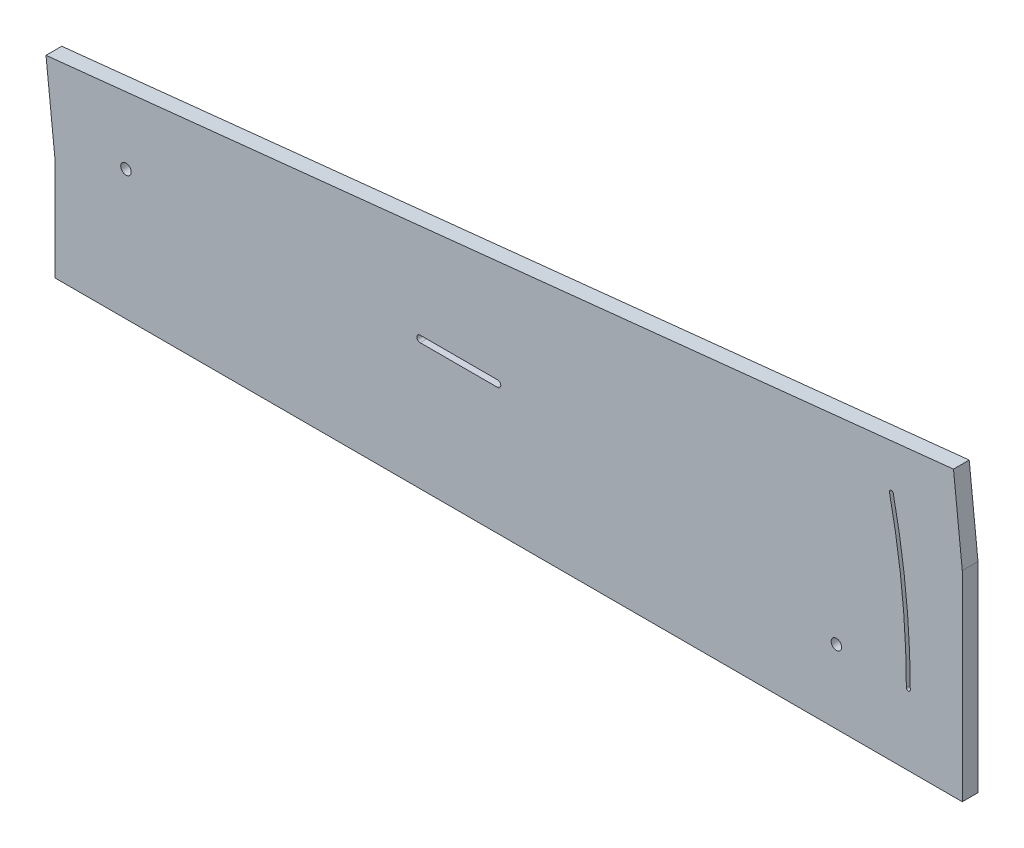
SolidWorks part; units mm, degrees
material "Pine"
ref_plane "Front Plane" through (0, 0, 0) normal (0, 0, 1) x (1, 0, 0)
ref_plane "Top Plane" through (0, 0, 0) normal (0, 1, 0) x (1, 0, 0)
ref_plane "Right Plane" through (0, 0, 0) normal (1, 0, 0) x (0, 0, -1)
sketch "Sketch1" plane through (0, 0, 0) normal (0, 0, 1) x (1, 0, 0)
  line L0 (-10.6201, 228.0434) -> (1088.2272, 343.5369)
  line L1 (1088.2272, 343.5369) -> (1098.8472, 242.4935)
  line L2 (1098.8472, 242.4935) -> (0, 127) construction
  line L3 (0, 127) -> (-10.6201, 228.0434)
  line L4 (0, 127) -> (0, 0)
  line L5 (0, 0) -> (1098.8472, 0)
  line L6 (1098.8472, 0) -> (1098.8472, 242.4935)
  line L7 (0, 127) -> (1098.8472, 127) construction
  dimension "D1" = 1104.9
  dimension "D2" = 101.6
  dimension "D3" = 6
  dimension "D4" = 127
extrude "Boss-Extrude1" add sketch "Sketch1" along normal blind 19.05
sketch "Sketch3" [suppressed] plane through (0, 0, 19.05) normal (0, 0, 1) x (1, 0, 0)
  line L0 (93.1354, -242.5766) -> (408.4688, -242.5766) construction
  line B0 (221.5466, -65.8912) -> (52.3501, -63.5412)
  arc B1 (731.486, 25.7569) -> (660.9874, 53.9563) centre (734.4449, 135.377) cw
  spline B2 degree 3 poles (52.3501, -63.5412) (59.4, -57.2747) (64.9444, -48.7137) (73.4997, -44.7416) (87.4583, -38.2608) (102.9844, -35.6165) (118.1487, -32.9919) (143.8059, -28.5512) (169.9355, -27.3805) (195.6971, -23.5921) (196.7931, -23.4309) (197.0131, -21.6398) (198.0471, -21.2421) (217.473, -13.7706) (237.3699, -7.5641) (256.7958, -0.0926) (257.8298, 0.3051) (258.1296, 1.8164) (259.1458, 2.2574) (299.7181, 19.8642) (340.9438, 35.9565) (381.3433, 53.9563) (420.0735, 71.2124) (456.7375, 93.258) (496.4909, 108.0052) (506.0382, 111.547) (516.883, 108.7307) (527.0402, 108.0052) (528.1452, 107.9263) (528.3844, 106.1195) (529.3902, 105.6552) (548.8157, 96.6896) (568.7134, 88.7714) (588.1389, 79.8058) (589.1448, 79.3416) (589.5464, 78.038) (590.4889, 77.4558) (616.2054, 61.5721) (640.7876, 43.5367) (668.0373, 30.4568) (680.3702, 24.537) (694.3438, 22.0676) (707.9865, 21.057) (715.9529, 20.4669) (723.6528, 24.1903) (731.486, 25.7569) knots 0 0 0 0 1 1 1 2 2 2 3 3 3 4 4 4 5 5 5 6 6 6 7 7 7 8 8 8 9 9 9 10 10 10 11 11 11 12 12 12 13 13 13 14 14 14 15 15 15 15
  spline B3 degree 3 poles (660.9874, 53.9563) (664.904, 57.0896) (668.3424, 60.939) (672.7372, 63.3561) (684.0984, 69.6048) (695.5775, 76.0455) (707.9865, 79.8058) (721.6663, 83.9512) (736.1859, 84.5057) (750.2856, 86.8556) knots 0 0 0 0 1 1 1 2 2 2 3 3 3 3
  spline B4 degree 3 poles (750.2856, 86.8556) (751.0689, 86.0723) (751.5704, 84.81) (752.6355, 84.5057) (762.6842, 81.6346) (773.1362, 80.3269) (783.1849, 77.4558) (784.25, 77.1515) (784.5831, 75.6728) (785.5348, 75.1059) (821.429, 53.7222) (856.7292, 31.2479) (893.6326, 11.6572) (920.2584, -2.4775) (948.3154, -13.7409) (975.8809, -25.942) (996.1025, -34.8926) (1017.2003, -41.9018) (1036.9796, -51.7915) (1042.4516, -54.5275) (1045.5354, -60.9541) (1051.0793, -63.5412) (1057.6236, -66.5952) (1065.3776, -65.9574) (1072.2289, -68.2411) (1079.5478, -70.6808) (1088.3258, -71.811) (1093.3784, -77.6409) (1099.3832, -84.5695) (1099.645, -94.8739) (1102.7782, -103.4904) knots 0 0 0 0 1 1 1 2 2 2 3 3 3 4 4 4 5 5 5 6 6 6 7 7 7 8 8 8 9 9 9 10 10 10 10
sketch_block_instance "Block1-1"
sketch_block "Block1"
sketch "Sketch5" [suppressed] plane through (0, 0, 19.05) normal (0, 0, 1) x (1, 0, 0)
  line L0 (13.2751, -329.5043) -> (1112.1224, -329.5043) construction
sketch_block_instance "KSU Logo-1"
sketch_block "KSU Logo"
sketch "Sketch6" [suppressed] plane through (0, 0, 19.05) normal (0, 0, 1) x (1, 0, 0)
  line L0 (13.2751, -329.5043) -> (1112.2917, -329.5043)
  arc A0 (644.4772, -182.5663) -> (719.2506, -209.2264) centre (717.9864, -94.5838) ccw construction
  arc A1 (644.4772, -182.5663) -> (719.2506, -209.2264) centre (717.9864, -94.5838) ccw
  spline S0 degree 3 poles (-1280.3103, 1192.4596) (70.4152, -589.6915) (-25.4983, -339.7665) (34.624, -309.0232) (48.9497, -301.6978) (65.0655, -298.3182) (80.8041, -294.9736) (107.4329, -289.3148) (134.6851, -287.0536) (161.4489, -282.072) (162.5875, -281.8601) (162.7462, -279.9801) (163.8106, -279.5235) (183.8089, -270.9458) (204.3494, -263.671) (224.3477, -255.0934) (225.4121, -254.6368) (225.6653, -253.046) (226.7094, -252.5449) (268.3976, -232.5382) (310.8285, -214.0878) (352.3204, -193.6774) (392.0981, -174.1104) (429.5267, -149.6216) (470.4728, -132.635) (480.3066, -128.5554) (491.7485, -131.0668) (502.3891, -131.4212) (503.5466, -131.4597) (503.8683, -133.3379) (504.9375, -133.7829) (525.5885, -142.3779) (546.6911, -149.8598) (567.3421, -158.4547) (568.4113, -158.8998) (568.8827, -160.2457) (569.8905, -160.8165) (597.3888, -176.3891) (623.7875, -194.2548) (652.7762, -206.8372) (665.8961, -212.5318) (680.5931, -214.5566) (694.8864, -215.0703) (756.2736, -217.2767) (793.3222, 23.7242) (1074.5457, -2175.2338) knots -5.847463 -5.847463 -5.847463 -5.847463 1 1 1 2 2 2 3 3 3 4 4 4 5 5 5 6 6 6 7 7 7 8 8 8 9 9 9 10 10 10 11 11 11 12 12 12 13 13 13 14 14 14 21.354953 21.354953 21.354953 21.354953 only from (13.2751, -329.5043) to (719.2506, -209.2264) construction
  spline S1 degree 3 poles (13.2751, -329.5043) (20.3914, -322.6772) (25.8438, -313.5129) (34.624, -309.0232) (48.9497, -301.6978) (65.0655, -298.3182) (80.8041, -294.9736) (107.4329, -289.3148) (134.6851, -287.0536) (161.4489, -282.072) (162.5875, -281.8601) (162.7462, -279.9801) (163.8106, -279.5235) (183.8089, -270.9458) (204.3494, -263.671) (224.3477, -255.0934) (225.4121, -254.6368) (225.6653, -253.046) (226.7094, -252.5449) (268.3976, -232.5382) (310.8285, -214.0878) (352.3204, -193.6774) (392.0981, -174.1104) (429.5267, -149.6216) (470.4728, -132.635) (480.3066, -128.5554) (491.7485, -131.0668) (502.3891, -131.4212) (503.5466, -131.4597) (503.8683, -133.3379) (504.9375, -133.7829) (525.5885, -142.3779) (546.6911, -149.8598) (567.3421, -158.4547) (568.4113, -158.8998) (568.8827, -160.2457) (569.8905, -160.8165) (597.3888, -176.3891) (623.7875, -194.2548) (652.7762, -206.8372) (665.8961, -212.5318) (680.5931, -214.5566) (694.8864, -215.0703) (703.2328, -215.3703) (711.1292, -211.1744) (719.2506, -209.2264) knots 0 0 0 0 1 1 1 2 2 2 3 3 3 4 4 4 5 5 5 6 6 6 7 7 7 8 8 8 9 9 9 10 10 10 11 11 11 12 12 12 13 13 13 14 14 14 15 15 15 15
  spline S2 degree 3 poles (-241.4428, -1889.1202) (782.5147, -13.4023) (726.4576, -143.9324) (739.0123, -147.0086) (749.6246, -149.6088) (760.5963, -150.5598) (771.2087, -153.1601) (772.3336, -153.4357) (772.7403, -154.9673) (773.7571, -155.5218) (812.107, -176.4361) (849.8797, -198.5135) (889.2127, -217.5144) (917.5914, -231.2236) (947.3515, -241.8763) (976.6351, -253.528) (998.1172, -262.0756) (1020.4374, -268.5602) (1041.4947, -278.1065) (1047.3203, -280.7475) (1050.7974, -287.3391) (1056.6922, -289.8218) (1063.6506, -292.7524) (1071.7263, -291.7779) (1078.9748, -293.8916) (1086.7181, -296.1496) (1095.9338, -296.9816) (1101.4442, -302.8717) (1143.8023, -348.1486) (940.7534, -550.5313) (2873.3021, 614.2618) knots -10.160638 -10.160638 -10.160638 -10.160638 1 1 1 2 2 2 3 3 3 4 4 4 5 5 5 6 6 6 7 7 7 8 8 8 9 9 9 15.468178 15.468178 15.468178 15.468178 only from (736.4638, -144.6469) to (1112.2917, -329.5043) construction
  spline S3 degree 3 poles (-635.8429, 1351.8798) (668.935, -363.0189) (612.6207, -198.5602) (656.3792, -172.2791) (668.0005, -165.2994) (679.7373, -158.1144) (692.5521, -153.6928) (801.1717, -116.2149) (970.0813, -298.5423) (503.9584, 1834.3294) knots -8.734019 -8.734019 -8.734019 -8.734019 1 1 1 2 2 2 9.688637 9.688637 9.688637 9.688637 only from (644.4772, -182.5663) to (736.4638, -144.6469) construction
  spline S4 degree 3 poles (736.4638, -144.6469) (737.3133, -145.4341) (737.8874, -146.733) (739.0123, -147.0086) (749.6246, -149.6088) (760.5963, -150.5598) (771.2087, -153.1601) (772.3336, -153.4357) (772.7403, -154.9673) (773.7571, -155.5218) (812.107, -176.4361) (849.8797, -198.5135) (889.2127, -217.5144) (917.5914, -231.2236) (947.3515, -241.8763) (976.6351, -253.528) (998.1172, -262.0756) (1020.4374, -268.5602) (1041.4947, -278.1065) (1047.3203, -280.7475) (1050.7974, -287.3391) (1056.6922, -289.8218) (1063.6506, -292.7524) (1071.7263, -291.7779) (1078.9748, -293.8916) (1086.7181, -296.1496) (1095.9338, -296.9816) (1101.4442, -302.8717) (1107.9929, -309.8716) (1108.6758, -320.6267) (1112.2917, -329.5043) knots 0 0 0 0 1 1 1 2 2 2 3 3 3 4 4 4 5 5 5 6 6 6 7 7 7 8 8 8 9 9 9 10 10 10 10
  spline S5 degree 3 poles (644.4772, -182.5663) (648.4446, -179.1372) (651.8838, -174.979) (656.3792, -172.2791) (668.0005, -165.2994) (679.7373, -158.1144) (692.5521, -153.6928) (706.6794, -148.8184) (721.8266, -147.6622) (736.4638, -144.6469) knots 0 0 0 0 1 1 1 2 2 2 3 3 3 3
extrude "Cut-Extrude1" [suppressed] cut sketch "Sketch6" against normal through all
sketch "Sketch7" plane through (0, 0, 19.05) normal (0, 0, 1) x (1, 0, 0)
  line L0 (0, 127) -> (1098.8472, 242.4935) construction
  line L1 (-5.31, 177.5217) -> (57.8421, 184.1593) construction
  line L2 (-10.6201, 228.0434) -> (0, 127) construction
  line L3 (57.8421, 184.1593) -> (1029.2612, 235.0692) construction
  line L4 (57.8421, 184.1593) -> (1018.6182, 336.3312) construction
  line L5 (57.8421, 184.1593) -> (1030.3851, 286.3777) construction
  line L6 (1098.8472, 242.4935) -> (1088.2272, 343.5369) construction
  line L7 (1018.6182, 336.3312) -> (1029.2612, 235.0692) construction
  line L8 (1025.075, 336.8994) -> (1035.6951, 235.8559) construction
  line L9 (1088.2272, 343.5369) -> (-10.6201, 228.0434) construction
  arc A0 (1018.6182, 336.3312) -> (1029.2612, 235.0692) centre (828.2982, 265.1375) cw
  arc A1 (1016.3879, 335.4969) -> (1026.9062, 235.4216) centre (828.2982, 265.1375) cw
  arc A2 (1020.8485, 337.1656) -> (1031.6163, 234.7168) centre (828.2982, 265.1375) cw
  arc A3 (1016.3879, 335.4969) -> (1020.8485, 337.1656) centre (1018.6182, 336.3312) cw
  arc A4 (1026.9062, 235.4216) -> (1031.6163, 234.7168) centre (1029.2612, 235.0692) ccw
  circle A5 centre (57.8421, 184.1593) radius 2.3812
  point P9 (1030.3851, 286.3777)
  point P12 (1023.9397, 285.7002)
  point P15 (1030.3851, 286.3777)
  dimension "D3" = 203.2
  dimension "D5" = 4.7625
  dimension "D6" = 4.7625
  dimension "D1" = 63.5
  dimension "D2" = 3
  dimension "D4" = 63.5
extrude "Cut-Extrude2" [suppressed] cut sketch "Sketch7" against normal through all
sketch "Sketch8" plane through (0, 0, 19.05) normal (0, 0, 1) x (1, 0, 0)
  line L0 (442.416, 157.1625) -> (536.0785, 157.1625) construction
  line L1 (540.0472, 0) -> (540.0472, 285.9209) construction
  line L6 (0, 0) -> (1098.8472, 0) construction
  line L7 (1088.2272, 343.5369) -> (-10.6201, 228.0434) construction
  line L8 (442.416, 161.1312) -> (536.0785, 161.1312)
  line L9 (1098.8472, 242.4935) -> (0, 127) construction
  line L10 (0, 127) -> (1098.8472, 127) construction
  line L11 (1098.8472, 0) -> (1098.8472, 242.4935) construction
  line L12 (86.1972, 157.1625) -> (442.416, 157.1625) construction
  line L13 (0, 127) -> (0, 0) construction
  line L14 (442.416, 153.1937) -> (536.0785, 153.1937)
  arc A0 (442.416, 161.1312) -> (442.416, 153.1937) centre (442.416, 157.1625) ccw
  arc A1 (536.0785, 153.1937) -> (536.0785, 161.1312) centre (536.0785, 157.1625) ccw
  circle A3 centre (86.1972, 157.1625) radius 6.35
  point P1 (489.2472, 157.1625)
  point P15 (540.0472, 157.1625)
  point P17 (438.4472, 157.1625)
  dimension "D6" = 12.7
  dimension "D1" = 7.9375
  dimension "D2" = 438.4472
  dimension "D3" = 101.6
  dimension "D4" = 157.1625
  dimension "D5" = 86.1972
extrude "Cut-Extrude3" cut sketch "Sketch8" against normal through all
sketch "Sketch9" plane through (0, 0, 19.05) normal (0, 0, 1) x (1, 0, 0)
  line L4 (0, 0) -> (1098.8472, 0) construction
  line L5 (1098.8472, 0) -> (1098.8472, 242.4935) construction
  arc A7 (1012.9862, 281.1663) -> (1033.523, 85.7709) centre (93.723, 85.7709) cw construction
  arc A8 (1012.9862, 281.1663) -> (1033.523, 85.7709) centre (93.723, 85.7709) cw construction
  arc A9 (1035.9043, 85.7709) -> (1015.3154, 281.6614) centre (93.723, 85.7709) ccw
  arc A10 (1031.1418, 85.7709) -> (1010.6569, 280.6712) centre (93.723, 85.7709) ccw
  arc A11 (1031.1418, 85.7709) -> (1035.9043, 85.7709) centre (1033.523, 85.7709) ccw
  arc A12 (1015.3154, 281.6614) -> (1010.6569, 280.6712) centre (1012.9862, 281.1663) ccw
  point P0 (1033.523, 85.7709)
  point P7 (1012.9862, 281.1663)
  point P12 (1028.3747, 184.0067)
  point P15 (1028.3747, 184.0067)
  dimension "D7" = 4.7625
  dimension "D1" = 281.1663
  dimension "D2" = 184.0067
  dimension "D3" = 85.7709
  dimension "D4" = 65.3242
  dimension "D5" = 70.4725
  dimension "D6" = 85.8611
extrude "Cut-Extrude4" cut sketch "Sketch9" against normal through all
sketch "Sketch10" plane through (0, 0, 19.05) normal (0, 0, 1) x (1, 0, 0)
  line L0 (0, 0) -> (1098.8472, 0) construction
  line L1 (1098.8472, 0) -> (1098.8472, 242.4935) construction
  circle A0 centre (946.4472, 88.9) radius 6.35
  dimension "D1" = 12.7
  dimension "D2" = 152.4
  dimension "D3" = 88.9
extrude "Cut-Extrude5" cut sketch "Sketch10" against normal through all
